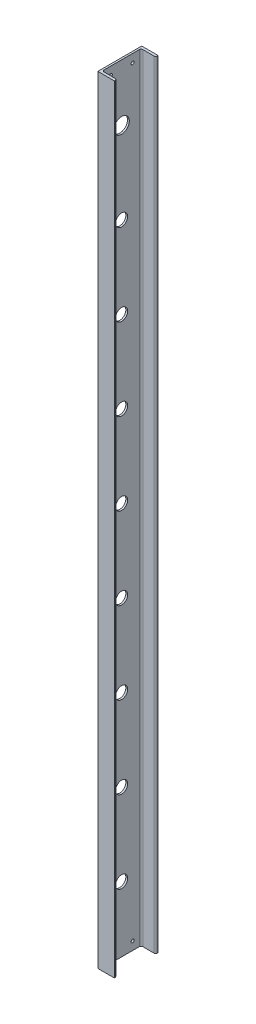
SolidWorks part; units mm, degrees
material "ASTM A36 Steel"
ref_plane "Front Plane" through (0, 0, 0) normal (0, 0, 1) x (1, 0, 0)
ref_plane "Top Plane" through (0, 0, 0) normal (0, 1, 0) x (1, 0, 0)
ref_plane "Right Plane" through (0, 0, 0) normal (1, 0, 0) x (0, 0, -1)
sketch "Sketch1" plane through (0, 0, 0) normal (0, 1, 0) x (1, 0, 0)
  line L0 (-38.4426, 80.9836) -> (-113.4426, 80.9836)
  line L1 (-113.4426, 80.9836) -> (-113.4426, -119.0164)
  line L2 (-113.4426, -119.0164) -> (-38.4426, -119.0164)
  line L3 (-38.4426, -119.0164) -> (-38.4426, -115.5164)
  line L4 (-46.4426, -107.5164) -> (-96.9426, -107.5164)
  line L5 (-104.9426, -99.5164) -> (-104.9426, 61.4836)
  line L6 (-96.9426, 69.4836) -> (-46.4426, 69.4836)
  line L7 (-38.4426, 80.9836) -> (-38.4426, 77.4836)
  arc A0 (-38.4426, -115.5164) -> (-46.4426, -107.5164) centre (-46.4426, -115.5164) ccw
  arc A1 (-96.9426, -107.5164) -> (-104.9426, -99.5164) centre (-96.9426, -99.5164) cw
  arc A2 (-104.9426, 61.4836) -> (-96.9426, 69.4836) centre (-96.9426, 61.4836) cw
  arc A3 (-46.4426, 69.4836) -> (-38.4426, 77.4836) centre (-46.4426, 77.4836) ccw
  dimension "D7" = 8
  dimension "D1" = 200
  dimension "D2" = 75
  dimension "D3" = 75
  dimension "D4" = 8.5
  dimension "D5" = 11.5
  dimension "D6" = 11.5
extrude "Boss-Extrude1" add sketch "Sketch1" along normal blind 3540
sketch "Sketch3" plane through (-113.4426, 0, 0) normal (-1, 0, 0) x (0, 0, 1)
  line L0 (-80.9836, 3540) -> (-80.9836, 0) construction
  line L1 (-80.9836, 0) -> (119.0164, 0) construction
  circle A0 centre (-30.9836, 37.5) radius 7
  circle A1 centre (69.0164, 37.5) radius 7.5
  dimension "D1" = 15
  dimension "D2" = 14
  dimension "D3" = 100
  dimension "D4" = 50
  dimension "D5" = 37.5
  dimension "D6" = 37.5
extrude "Cut-Extrude2" cut sketch "Sketch3" against normal blind 3540
ref_plane "Plane1" through (0, 1770, 0) normal (0, -1, 0) x (-1, 0, 0)
mirror "Mirror1" about plane through (0, 1770, 0) normal (0, -1, 0) of "Cut-Extrude2"
sketch "Sketch4" plane through (-104.9426, 0, 0) normal (1, 0, 0) x (0, 0, -1)
  line L0 (-99.5164, 0) -> (61.4836, 0) construction
  circle A0 centre (-19.0164, 297) radius 27.5
  dimension "D1" = 55
  dimension "D2" = 297
extrude "Cut-Extrude3" cut sketch "Sketch4" against normal through all both and the other way through all
pattern_linear "LPattern2" count 9 spacing 373 along (0, 1, 0) of "Cut-Extrude3"
sketch "Sketch5" plane through (-113.4426, 0, 0) normal (-1, 0, 0) x (0, 0, 1)
  circle A0 centre (19.0164, 297) radius 35
  dimension "D1" = 70
sketch "Sketch6" plane through (-104.9426, 0, 0) normal (1, 0, 0) x (0, 0, -1)
  circle A0 centre (-19.0164, 3281) radius 35
  dimension "D1" = 70
extrude "Cut-Extrude5" cut sketch "Sketch6" against normal blind 20
